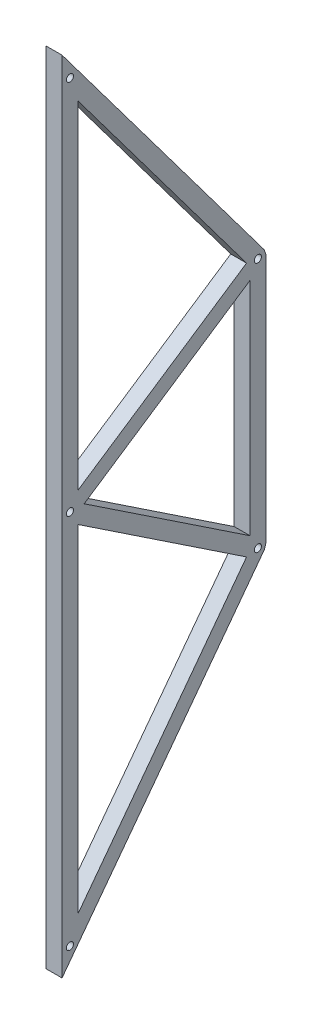
SolidWorks part; units mm, degrees
material "6061-T6 (SS)"
ref_plane "Front Plane" through (0, 0, 0) normal (1, 0, 0) x (0, 1, 0)
ref_plane "Top Plane" through (0, 0, 0) normal (0, 0, 1) x (0, 1, 0)
ref_plane "Right Plane" through (0, 0, 0) normal (0, 1, 0) x (-1, 0, 0)
sketch "Sketch1" plane through (0, 0, 0) normal (1, 0, 0) x (0, 1, 0)
  line L0 (-600, 0) -> (-200, -300) construction
  line L1 (-200, -300) -> (200, -300) construction
  line L2 (200, -300) -> (600, 0) construction
  line L3 (600, 0) -> (0, 0) construction
  line L4 (0, 0) -> (-600, 0) construction
  line L5 (-200, -300) -> (0, 0) construction
  line L6 (200, -300) -> (0, 0) construction
  line L7 (0, 12.615) -> (-637.845, 12.615)
  line L8 (-637.845, 12.615) -> (-207.569, -310.092)
  line L9 (176.4287, -287.385) -> (0, -22.742)
  line L10 (-200, -312.615) -> (200, -312.615)
  line L12 (207.569, -310.092) -> (637.845, 12.615)
  line L13 (637.845, 12.615) -> (0, 12.615)
  line L15 (-562.155, -12.615) -> (-203.0992, -281.9068)
  line L17 (-176.4287, -287.385) -> (176.4287, -287.385)
  line L18 (203.0992, -281.9068) -> (562.155, -12.615)
  line L19 (203.0992, -281.9068) -> (23.5713, -12.615)
  line L20 (562.155, -12.615) -> (23.5713, -12.615)
  line L21 (-200, -312.615) -> (-207.569, -310.092)
  line L22 (207.569, -310.092) -> (200, -312.615)
  line L24 (-562.155, -12.615) -> (-192.431, -289.908) construction
  line L25 (-200, -287.385) -> (200, -287.385) construction
  line L26 (-203.0992, -281.9068) -> (-23.5713, -12.615)
  line L27 (562.155, -12.615) -> (0, -12.615) construction
  line L28 (-176.4287, -287.385) -> (0, -22.742)
  line L29 (192.431, -289.908) -> (562.155, -12.615) construction
  line L30 (0, -12.615) -> (-562.155, -12.615) construction
  line L31 (-23.5713, -12.615) -> (-562.155, -12.615)
  circle A0 centre (-600, 0) radius 5.71
  circle A1 centre (0, 0) radius 5.71
  circle A2 centre (-200, -300) radius 5.71
  circle A3 centre (200, -300) radius 5.71
  circle A4 centre (600, 0) radius 5.71
  point P0 (0, 0)
  point P1 (-600, 0)
  point P3 (600, 0)
  point P4 (200, -300)
  point P5 (-200, -300)
  dimension "D8" = 11.42
  dimension "D1" = 600
  dimension "D2" = 600
  dimension "D3" = 400
  dimension "D4" = 400
  dimension "D5" = 300
  dimension "D6" = 12.615
  dimension "D7" = 12.615
extrude "Boss-Extrude1" add sketch "Sketch1" along normal blind 25.23
